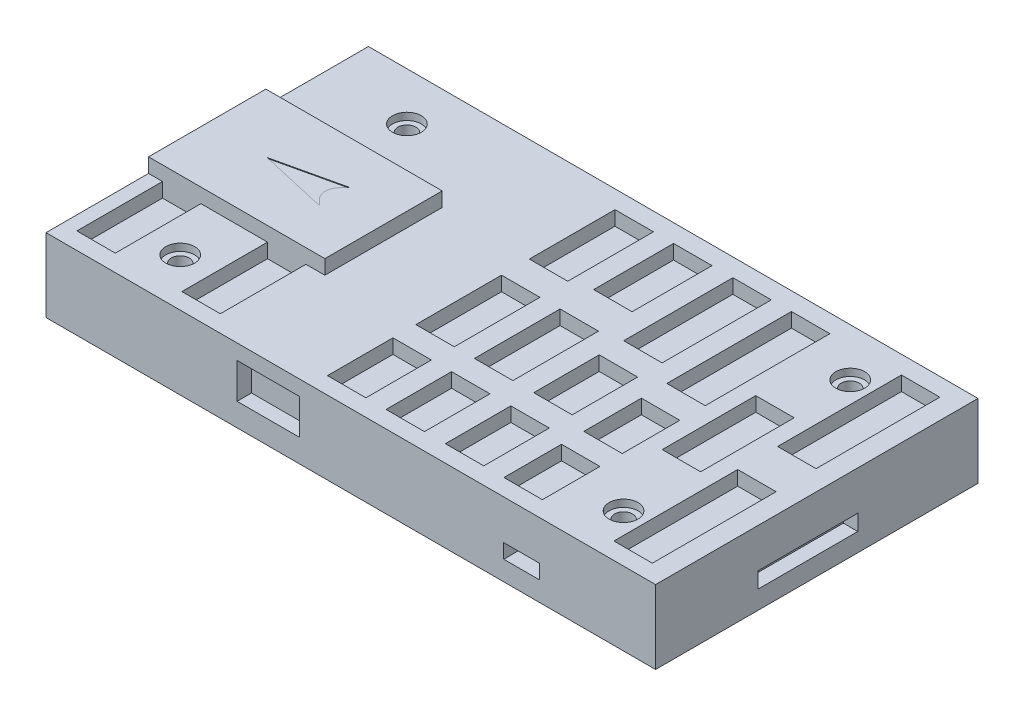
SolidWorks part; units mm, degrees
material "6061 Alloy"
ref_plane "Front Plane" through (0, 0, 0) normal (0, 0, 1) x (1, 0, 0)
ref_plane "Top Plane" through (0, 0, 0) normal (0, 1, 0) x (1, 0, 0)
ref_plane "Right Plane" through (0, 0, 0) normal (1, 0, 0) x (0, 0, -1)
sketch "Sketch1" plane through (0, 0, 0) normal (0, 1, 0) x (1, 0, 0)
  line L1 (-42.35, 22.4) -> (42.35, 22.4)
  line L2 (-42.35, 22.4) -> (-42.35, -22.4)
  line L3 (-42.35, -22.4) -> (42.35, -22.4)
  line L4 (42.35, 22.4) -> (42.35, -22.4)
  line L5 (-42.35, 22.4) -> (42.35, -22.4) construction
  line L6 (-42.35, -22.4) -> (42.35, 22.4) construction
  point P0 (0, 0)
  dimension "D1" = 84.7
  dimension "D2" = 44.8
extrude "Boss-Extrude1" add sketch "Sketch1" along normal blind 10.22
sketch "Sketch2" plane through (0, 10.22, 0) normal (0, 1, 0) x (1, 0, 0)
  line L0 (-42.35, 22.4) -> (-42.35, -22.4) construction
  line L1 (-42.35, 8.15) -> (-17.85, 8.15)
  line L2 (-42.35, 8.15) -> (-42.35, -8.15)
  line L3 (-42.35, -8.15) -> (-17.85, -8.15)
  line L4 (-17.85, 8.15) -> (-17.85, -8.15)
  line L5 (-42.35, 8.15) -> (-17.85, -8.15) construction
  line L6 (-42.35, -8.15) -> (-17.85, 8.15) construction
  point P0 (-30.1, 0)
  dimension "D1" = 24.5
  dimension "D2" = 16.3
extrude "Boss-Extrude2" add sketch "Sketch2" along normal blind 2
sketch "Sketch3" plane through (0, 10.22, 0) normal (0, 1, 0) x (1, 0, 0)
  line L0 (-42.35, -8.15) -> (-17.85, -8.15) construction
  line L1 (-40.41, -8.15) -> (-35.07, -8.15)
  line L2 (-40.41, -8.15) -> (-40.41, -20.05)
  line L4 (-35.07, -8.15) -> (-35.07, -20.05)
  line L5 (-40.41, -8.15) -> (-35.07, -20.05) construction
  line L6 (-40.41, -20.05) -> (-35.07, -8.15) construction
  line L7 (-25.82, -20.05) -> (-20.48, -20.05)
  line L8 (-42.35, -8.15) -> (-42.35, -22.4) construction
  line L9 (-40.41, -20.05) -> (-35.07, -20.05)
  line L10 (-25.82, -8.15) -> (-25.82, -20.05)
  line L11 (-42.35, -8.15) -> (-17.85, -8.15) construction
  line L12 (-25.82, -8.15) -> (-20.48, -8.15)
  line L13 (-20.48, -8.15) -> (-20.48, -20.05)
  line L14 (-20.48, -20.05) -> (-5.59, -20.05) construction
  line L15 (-5.59, -20.05) -> (-5.59, -10.95)
  line L16 (-5.59, -10.95) -> (-0.25, -10.95)
  line L17 (-0.25, -10.95) -> (-0.25, -20.05)
  line L18 (-0.25, -20.05) -> (-5.59, -20.05)
  line L19 (7.89, -20.05) -> (2.55, -20.05)
  line L20 (2.55, -20.05) -> (2.55, -10.95)
  line L21 (2.55, -10.95) -> (7.89, -10.95)
  line L22 (7.89, -10.95) -> (7.89, -20.05)
  line L23 (16.13, -20.05) -> (10.79, -20.05)
  line L24 (10.79, -20.05) -> (10.79, -10.95)
  line L25 (10.79, -10.95) -> (16.13, -10.95)
  line L26 (16.13, -10.95) -> (16.13, -20.05)
  line L27 (18.93, -12.05) -> (18.93, -20.05)
  line L28 (18.93, -12.05) -> (24.27, -12.05)
  line L29 (24.27, -12.05) -> (24.27, -20.05)
  line L30 (24.27, -20.05) -> (18.93, -20.05)
  line L31 (-42.35, -22.4) -> (42.35, -22.4) construction
  line L32 (21.6, -12.05) -> (21.6, -8.95) construction
  line L33 (18.93, -8.95) -> (24.27, -8.95)
  line L34 (18.93, -8.95) -> (18.93, -0.95)
  line L35 (18.93, -0.95) -> (24.27, -0.95)
  line L36 (24.27, -0.95) -> (24.27, -8.95)
  line L37 (34.21, -2.85) -> (34.21, -20.05)
  line L38 (34.21, -20.05) -> (39.55, -20.05)
  line L39 (39.55, -20.05) -> (39.55, -2.85)
  line L40 (39.55, -2.85) -> (34.21, -2.85)
  line L42 (42.35, 22.4) -> (-42.35, 22.4) construction
  line L43 (-5.59, -10.95) -> (-5.59, -7.77) construction
  line L44 (-5.59, -7.77) -> (-5.59, 4.13)
  line L45 (-5.59, 4.13) -> (-0.25, 4.13)
  line L46 (-5.59, -7.77) -> (-0.25, -7.77)
  line L47 (-0.25, -7.77) -> (-0.25, 4.13)
  line L48 (2.55, -7.77) -> (2.55, 4.13)
  line L49 (2.55, 4.13) -> (7.89, 4.13)
  line L50 (7.89, 4.13) -> (7.89, -7.77)
  line L51 (7.89, -7.77) -> (2.55, -7.77)
  line L52 (10.79, -7.77) -> (10.79, 1.33)
  line L53 (10.79, 1.33) -> (16.13, 1.33)
  line L54 (16.13, 1.33) -> (16.13, -7.77)
  line L55 (16.13, -7.77) -> (10.79, -7.77)
  line L56 (-5.59, 4.13) -> (-5.59, 8) construction
  line L57 (-5.59, 8) -> (-5.59, 19.9)
  line L58 (-5.59, 19.9) -> (-0.25, 19.9)
  line L59 (-0.25, 19.9) -> (-0.25, 8)
  line L60 (-0.25, 8) -> (-5.59, 8)
  line L61 (-0.25, 19.9) -> (2.55, 19.9) construction
  line L62 (2.55, 19.9) -> (2.55, 8.8)
  line L63 (2.55, 8.8) -> (7.89, 8.8)
  line L64 (7.89, 8.8) -> (7.89, 19.9)
  line L65 (7.89, 19.9) -> (2.55, 19.9)
  line L66 (42.35, -22.4) -> (42.35, 22.4) construction
  line L67 (7.89, 19.9) -> (10.79, 19.9) construction
  line L68 (10.79, 19.9) -> (10.79, 4.73)
  line L69 (10.79, 4.73) -> (16.13, 4.73)
  line L70 (16.13, 4.73) -> (16.13, 19.9)
  line L71 (16.13, 19.9) -> (10.79, 19.9)
  line L72 (16.13, 19.9) -> (18.93, 19.9) construction
  line L73 (18.93, 19.9) -> (18.93, 2.58)
  line L74 (18.93, 2.58) -> (24.27, 2.58)
  line L75 (24.27, 2.58) -> (24.27, 19.9)
  line L76 (24.27, 19.9) -> (18.93, 19.9)
  line L77 (24.27, 19.9) -> (26.57, 19.9) construction
  line L78 (26.57, 22.4) -> (26.57, 7.3) construction
  line L79 (26.57, 7.3) -> (31.91, 7.3)
  line L80 (26.57, 7.3) -> (26.57, -5.7)
  line L81 (26.57, -5.7) -> (31.91, -5.7)
  line L82 (31.91, -5.7) -> (31.91, 7.3)
  line L83 (24.27, 19.9) -> (34.21, 19.9) construction
  line L84 (34.21, 19.9) -> (39.55, 19.9)
  line L85 (39.55, 19.9) -> (39.55, 2.7)
  line L86 (39.55, 2.7) -> (34.21, 2.7)
  line L87 (34.21, 2.7) -> (34.21, 19.9)
  point P0 (-37.74, -14.1)
  point P11 (-40.41, -14.1)
  dimension "D1" = 5.34
  dimension "D2" = 1.94
  dimension "D3" = 11.9
  dimension "D4" = 9.25
  dimension "D5" = 14.89
  dimension "D6" = 9.1
  dimension "D7" = 5.34
  dimension "D8" = 2.9
  dimension "D9" = 2.8
  dimension "D10" = 1.1
  dimension "D11" = 5.34
  dimension "D12" = 2.8
  dimension "D13" = 2.35
  dimension "D14" = 3.1
  dimension "D15" = 8
  dimension "D16" = 9.94
  dimension "D17" = 17.2
  dimension "D18" = 5.34
  dimension "D19" = 2.35
  dimension "D20" = 5.34
  dimension "D21" = 5.34
  dimension "D22" = 9.1
  dimension "D23" = 2.35
  dimension "D24" = 33.35
  dimension "D25" = 5.34
  dimension "D26" = 9.1
  dimension "D27" = 9.1
  dimension "D28" = 2.35
  dimension "D29" = 3.18
  dimension "D30" = 11.9
  dimension "D31" = 5.34
  dimension "D32" = 9.1
  dimension "D33" = 9.1
  dimension "D34" = 3.87
  dimension "D35" = 11.9
  dimension "D36" = 2.8
  dimension "D37" = 11.1
  dimension "D38" = 0.8
  dimension "D39" = 34.46
  dimension "D40" = 2.9
  dimension "D41" = 15.17
  dimension "D42" = 15.17
  dimension "D43" = 26.22
  dimension "D44" = 2.8
  dimension "D45" = 17.32
  dimension "D46" = 17.32
  dimension "D47" = 18.08
  dimension "D48" = 2.3
  dimension "D49" = 15.1
  dimension "D50" = 5.34
  dimension "D51" = 13
  dimension "D52" = 17.2
  dimension "D53" = 5.34
extrude "Cut-Extrude1" cut sketch "Sketch3" against normal blind 2
sketch "Sketch4" plane through (0, 0, 0) normal (0, -1, 0) x (1, 0, 0)
  line L0 (42.35, -22.4) -> (-42.35, -22.4) construction
  line L1 (-30.35, 15.75) -> (31.25, 15.75) construction
  line L2 (-30.35, 15.75) -> (-30.35, -15.75) construction
  line L3 (-30.35, -15.75) -> (31.25, -15.75) construction
  line L4 (31.25, 15.75) -> (31.25, -15.75) construction
  line L5 (-30.35, 15.75) -> (31.25, -15.75) construction
  line L6 (-30.35, -15.75) -> (31.25, 15.75) construction
  line L9 (-42.35, -22.4) -> (-42.35, 22.4) construction
  line L10 (42.35, 22.4) -> (42.35, -22.4) construction
  circle A0 centre (-30.35, 15.75) radius 1.25
  circle A1 centre (31.25, 15.75) radius 1.25
  circle A2 centre (31.25, -15.75) radius 1.25
  circle A3 centre (-30.35, -15.75) radius 1.25
  point P0 (0.45, 0)
  point P10 (0.45, 0)
  dimension "D5" = 2.5
  dimension "D1" = 12
  dimension "D2" = 31.5
  dimension "D3" = 11.1
  dimension "D4" = 6.65
extrude "Cut-Extrude2" cut sketch "Sketch4" against normal through all
sketch "Sketch5" plane through (0, 10.22, 0) normal (0, 1, 0) x (1, 0, 0)
  circle A0 centre (-30.35, 15.75) radius 2
  circle A1 centre (-30.35, -15.75) radius 2
  circle A2 centre (31.25, 15.75) radius 2
  circle A3 centre (31.25, -15.75) radius 2
  dimension "D1" = 4
  dimension "D2" = 4
  dimension "D3" = 4
extrude "Cut-Extrude3" cut sketch "Sketch5" against normal blind 1
sketch "Sketch6" plane through (0, 0, 22.4) normal (0, 0, 1) x (1, 0, 0)
  line L0 (-15.8, 8.12) -> (-15.8, 3.2)
  line L1 (-15.8, 3.2) -> (-7.16, 3.2)
  line L2 (-7.16, 3.2) -> (-7.16, 8.12)
  line L3 (-7.16, 8.12) -> (-15.8, 8.12)
  line L4 (-42.35, 10.22) -> (42.35, 10.22) construction
  line L5 (-42.35, 0) -> (42.35, 0) construction
  line L6 (-42.35, 10.22) -> (-42.35, 0) construction
  dimension "D1" = 8.64
  dimension "D2" = 2.1
  dimension "D3" = 3.2
  dimension "D4" = 26.55
extrude "Cut-Extrude4" cut sketch "Sketch6" against normal blind 2
sketch "Sketch7" plane through (0, 0, 22.4) normal (0, 0, 1) x (1, 0, 0)
  line L0 (21.25, 4.72) -> (26.25, 4.72)
  line L1 (26.25, 4.72) -> (26.25, 2.72)
  line L2 (26.25, 2.72) -> (21.25, 2.72)
  line L3 (21.25, 2.72) -> (21.25, 4.72)
  line L4 (42.35, 10.22) -> (42.35, 0) construction
  line L5 (-42.35, 10.22) -> (42.35, 10.22) construction
  dimension "D1" = 5
  dimension "D2" = 16.1
  dimension "D3" = 2
  dimension "D4" = 5.5
extrude "Cut-Extrude5" cut sketch "Sketch7" against normal blind 2
sketch "Sketch8" plane through (0, 0, -22.4) normal (0, 0, -1) x (-1, 0, 0)
  line L0 (-13.05, 4.85) -> (7.28, 4.85)
  line L1 (7.28, 4.85) -> (7.28, 1.75)
  line L2 (7.28, 1.75) -> (-13.05, 1.75)
  line L3 (-13.05, 1.75) -> (-13.05, 4.85)
  line L4 (-42.35, 10.22) -> (42.35, 10.22) construction
  line L5 (-42.35, 10.22) -> (-42.35, 0) construction
  line L6 (-25.95, 4.72) -> (-20.45, 4.72)
  line L7 (-20.45, 4.72) -> (-20.45, 2.72)
  line L8 (-20.45, 2.72) -> (-25.95, 2.72)
  line L9 (-25.95, 2.72) -> (-25.95, 4.72)
  line L10 (-42.35, 0) -> (42.35, 0) construction
  dimension "D1" = 20.33
  dimension "D2" = 3.1
  dimension "D3" = 5.37
  dimension "D4" = 29.3
  dimension "D5" = 5.5
  dimension "D6" = 2
  dimension "D7" = 16.4
  dimension "D8" = 2.72
extrude "Cut-Extrude6" cut sketch "Sketch8" against normal blind 2
sketch "Sketch9" plane through (42.35, 0, 0) normal (1, 0, 0) x (0, 0, -1)
  line L0 (-8.2, 4.76) -> (5.7, 4.76)
  line L1 (5.7, 4.76) -> (5.7, 2.56)
  line L2 (5.7, 2.56) -> (-8.2, 2.56)
  line L3 (-8.2, 2.56) -> (-8.2, 4.76)
  line L4 (-22.4, 0) -> (22.4, 0) construction
  line L5 (22.4, 10.22) -> (22.4, 0) construction
  dimension "D1" = 13.9
  dimension "D2" = 2.2
  dimension "D3" = 2.56
  dimension "D4" = 16.7
extrude "Cut-Extrude7" cut sketch "Sketch9" against normal blind 2
sketch "Sketch10" plane through (0, 12.22, 0) normal (0, 1, 0) x (1, 0, 0)
  line L0 (-34.0344, 0) -> (-24.6344, 2.15)
  line L1 (-24.6344, 2.15) -> (-25.3692, 1.3922)
  line L2 (-25.3692, -1.3922) -> (-24.6344, -2.15)
  line L3 (-24.6344, -2.15) -> (-34.0344, 0)
  line L4 (-17.85, 8.15) -> (-42.35, 8.15) construction
  line L5 (-42.35, -8.15) -> (-17.85, -8.15) construction
  line L6 (-42.35, 8.15) -> (-42.35, -8.15) construction
  arc A0 (-25.3692, -1.3922) -> (-25.3692, 1.3922) centre (-23.9333, 0) cw
  dimension "D2" = 2
  dimension "D7" = 18.4167
  dimension "D1" = 9.4
  dimension "D3" = 8.15
  dimension "D4" = 6
  dimension "D5" = 6
  dimension "D6" = 8.3156
extrude "Cut-Extrude8" cut sketch "Sketch10" against normal blind 0.1
